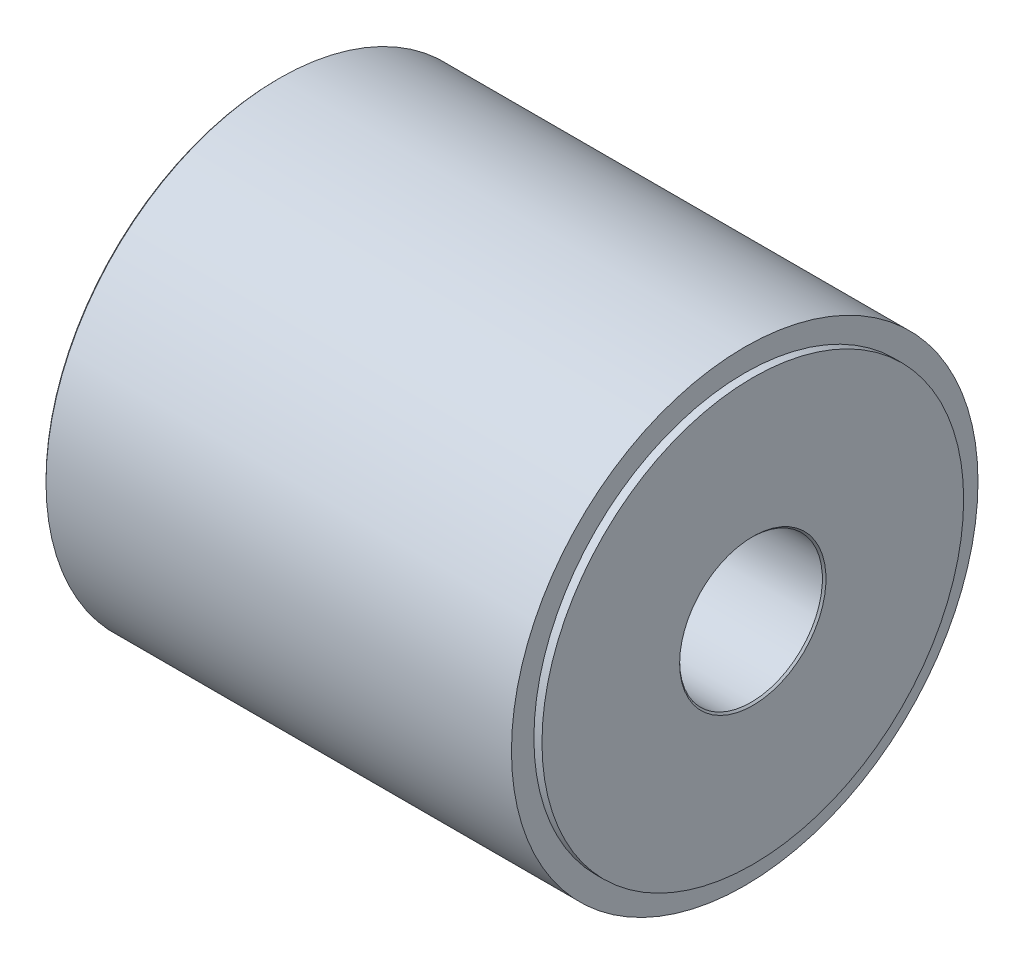
SolidWorks part; units mm, degrees
ref_plane "Front Plane" through (0, 0, 0) normal (0, 0, 1) x (1, 0, 0)
ref_plane "Top Plane" through (0, 0, 0) normal (0, 1, 0) x (1, 0, 0)
ref_plane "Right Plane" through (0, 0, 0) normal (1, 0, 0) x (0, 0, -1)
sketch "Sketch1" plane through (0, 0, 0) normal (0, 0, 1) x (1, 0, 0)
  line L0 (0, 0) -> (31.9657, 0) construction
  line L1 (0, 23.5) -> (1, 23.5)
  line L2 (1, 23.5) -> (1, 26)
  line L3 (1, 26) -> (53.08, 26)
  line L4 (53.08, 26) -> (53.08, 23.5)
  line L5 (53.08, 23.5) -> (53.98, 23.5)
  line L6 (53.98, 23.5) -> (53.98, 7.9565)
  line L7 (53.98, 7.9565) -> (0, 7.9565)
  line L8 (0, 7.9565) -> (0, 23.5)
  point P12 (53.08, 24.75)
  dimension "D1" = 53.98
  dimension "15.913mm" = 15.913
  dimension "D2" = 52
  dimension "D3" = 2.5
  dimension "D4" = 1
  dimension "D5" = 0.9
revolve "Revolve1" add sketch "Sketch1" angle 360 about L0
chamfer "Chamfer1" distance 0.2 angle 45 4 edges at (53.98, 0, 7.9565) (0, 0, 7.9565) (1, 0, 26) (0, 0, 23.5)
